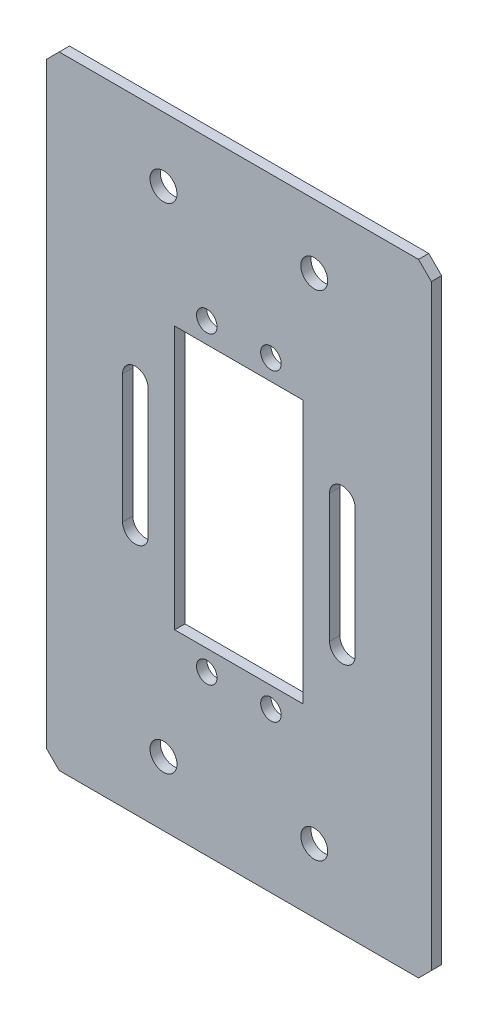
SolidWorks part; units mm, degrees
ref_plane "前视基准面" through (0, 0, 0) normal (0, 0, 1) x (1, 0, 0)
ref_plane "上视基准面" through (0, 0, 0) normal (0, 1, 0) x (1, 0, 0)
ref_plane "右视基准面" through (0, 0, 0) normal (1, 0, 0) x (0, 0, -1)
sketch "草图1" plane through (0, 0, 0) normal (0, 0, 1) x (1, 0, 0)
  line L0 (-115.2873, 0) -> (164.6781, 0) construction
  line L1 (0, 85.552) -> (0, -108.4834) construction
  line L2 (-30, 46.5) -> (-28, 48.5)
  line L3 (-28, 48.5) -> (28, 48.5)
  line L4 (-30, 46.5) -> (-30, -46.5)
  line L5 (-28, -48.5) -> (28, -48.5)
  line L6 (30, 46.5) -> (30, -46.5)
  line L7 (30, 46.5) -> (28, 48.5)
  line L8 (28, -48.5) -> (30, -46.5)
  line L9 (-28, -48.5) -> (-30, -46.5)
  line L10 (-18.1272, 10) -> (-18.1272, -10)
  line L11 (-10, 20.5) -> (10, 20.5)
  line L12 (-10, 20.5) -> (-10, -20.5)
  line L13 (-10, -20.5) -> (10, -20.5)
  line L14 (10, 20.5) -> (10, -20.5)
  line L15 (-14.1272, -10) -> (-14.1272, 10)
  line L16 (18.1272, 10) -> (18.1272, -10)
  line L17 (14.1272, -10) -> (14.1272, 10)
  circle A0 centre (-11.75, 38.5) radius 2.1
  circle A1 centre (-5, 23.7) radius 1.6
  arc A2 (-18.1272, -10) -> (-14.1272, -10) centre (-16.1272, -10) ccw
  arc A3 (-14.1272, 10) -> (-18.1272, 10) centre (-16.1272, 10) ccw
  circle A4 centre (-5, -23.7) radius 1.6
  circle A5 centre (-11.75, -38.5) radius 2.1
  arc A6 (18.1272, -10) -> (14.1272, -10) centre (16.1272, -10) cw
  arc A7 (14.1272, 10) -> (18.1272, 10) centre (16.1272, 10) cw
  circle A8 centre (11.75, -38.5) radius 2.1
  circle A9 centre (5, -23.7) radius 1.6
  circle A10 centre (5, 23.7) radius 1.6
  circle A11 centre (11.75, 38.5) radius 2.1
  dimension "D9" = 4.2
  dimension "D10" = 3.2
  dimension "D1" = 60
  dimension "D2" = 97
  dimension "D3" = 20
  dimension "D4" = 41
  dimension "D5" = 10
  dimension "D6" = 11.75
  dimension "D7" = 25
  dimension "D8" = 3.2
  dimension "D11" = 20
  dimension "D12" = 4
extrude "凸台-拉伸1" add sketch "草图1" along normal blind 1.6
